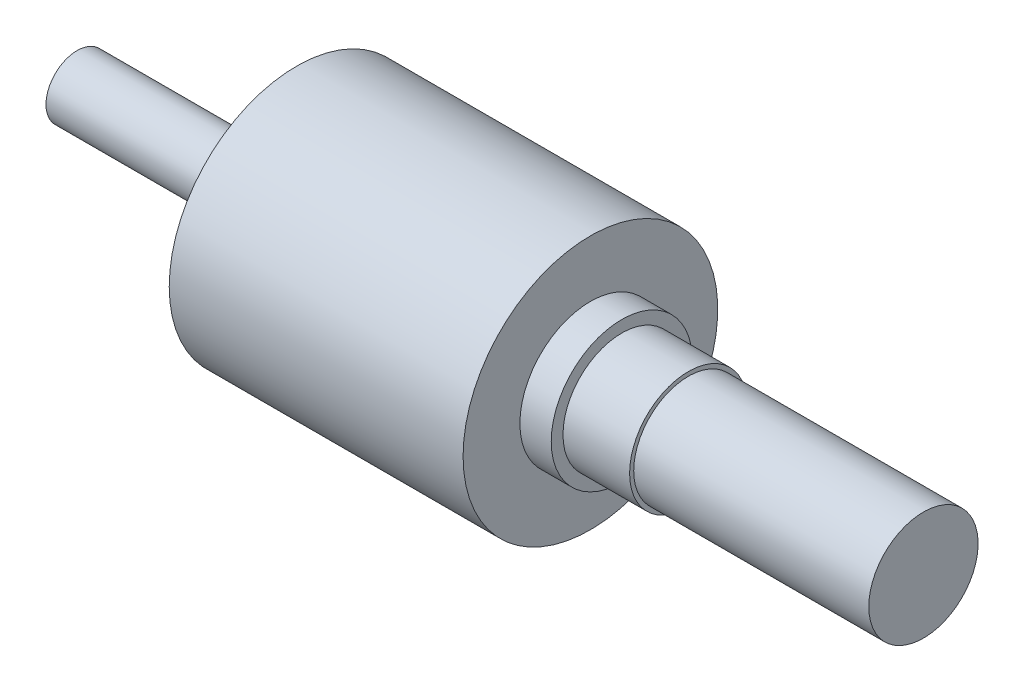
SolidWorks part; units mm, degrees
ref_plane "Ön Düzlem" through (0, 0, 0) normal (0, 0, 1) x (1, 0, 0)
ref_plane "Üst Düzlem" through (0, 0, 0) normal (0, 1, 0) x (1, 0, 0)
ref_plane "Sağ Düzlem" through (0, 0, 0) normal (1, 0, 0) x (0, 0, -1)
sketch "Çizim1" plane through (0, 0, 0) normal (0, 0, 1) x (1, 0, 0)
  line L0 (0, 0) -> (0, 3.975)
  line L1 (0, 3.975) -> (24, 3.975)
  line L2 (24, 3.975) -> (24, 6)
  line L3 (24, 6) -> (28, 6)
  line L4 (28, 6) -> (28, 16.25)
  line L5 (28, 16.25) -> (65.5, 16.25)
  line L6 (65.5, 16.25) -> (65.5, 9)
  line L7 (65.5, 9) -> (69.5, 9)
  line L8 (69.5, 9) -> (69.5, 7.5)
  line L10 (108, 6.975) -> (108, 0)
  line L11 (0, 0) -> (50000, 0) construction
  line L12 (0, 0) -> (108, 0)
  line L13 (69.5, 7.5) -> (78, 7.5)
  line L14 (78, 7.5) -> (78, 6.975)
  line L15 (78, 6.975) -> (108, 6.975)
  dimension "D1" = 3.975
  dimension "D2" = 28
  dimension "D3" = 4
  dimension "D4" = 6
  dimension "D5" = 37.5
  dimension "D6" = 6.975
  dimension "D7" = 7.5
  dimension "D8" = 16.25
  dimension "D9" = 4
  dimension "D10" = 8.5
  dimension "D11" = 9
  dimension "D12" = 30
revolve "Döndür1" add sketch "Çizim1" angle 360 about L11
